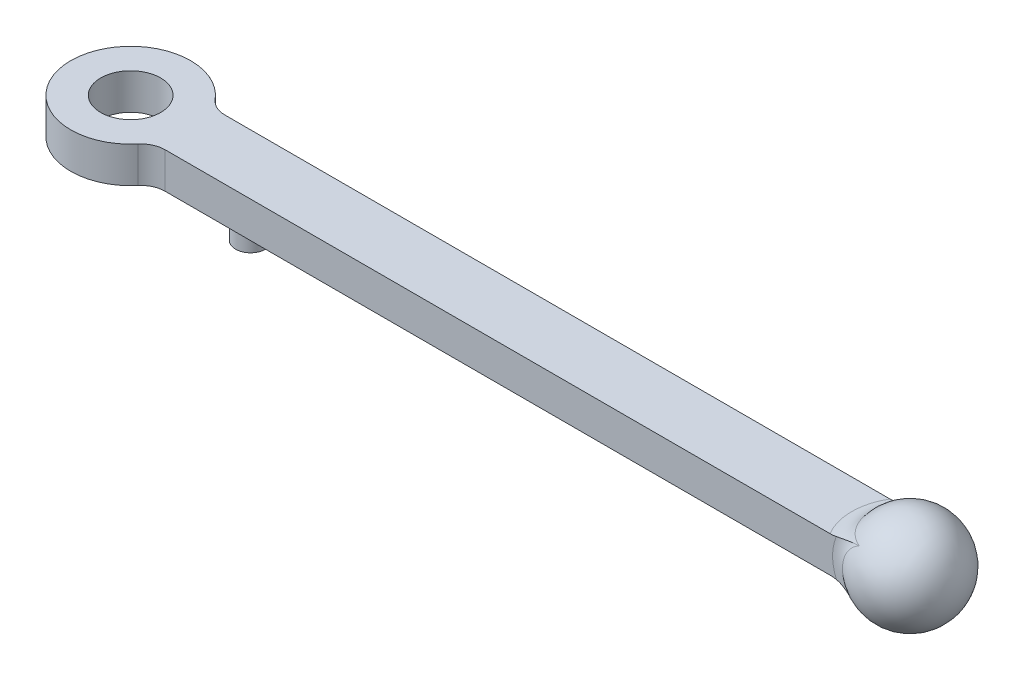
SolidWorks part; units mm, degrees
ref_plane "前视基准面" through (0, 0, 0) normal (0, 0, 1) x (1, 0, 0)
ref_plane "上视基准面" through (0, 0, 0) normal (0, 1, 0) x (1, 0, 0)
ref_plane "右视基准面" through (0, 0, 0) normal (1, 0, 0) x (0, 0, -1)
sketch "草图1" plane through (0, 0, 0) normal (0, 1, 0) x (1, 0, 0)
  line L0 (0, 0) -> (130, 0)
  line L2 (130, -5) -> (8.6603, -5)
  line L3 (130, -5) -> (130, 5)
  line L4 (130, 5) -> (8.6603, 5)
  line L5 (8.6603, -5) -> (8.6603, 5)
  circle A0 centre (0, 0) radius 10
  circle A1 centre (130, 0) radius 5
  dimension "D1" = 20
  dimension "D3" = 10
  dimension "D2" = 130
extrude "凸台-拉伸1" add sketch "草图1" along normal blind 6
ref_plane "基准面1" through (0, 3, 0) normal (0, 1, 0) x (1, 0, 0)
sketch "草图2" plane through (0, 3, 0) normal (0, 1, 0) x (1, 0, 0)
  line L0 (130, 0) -> (140, 0)
  line L1 (130, 0) -> (122, 0)
  line L2 (130, 5) -> (8.6603, 5)
  line L3 (8.6603, -5) -> (130, -5)
  line L4 (130, 5) -> (8.6603, 5)
  line L5 (8.6603, -5) -> (130, -5)
  line L6 (138, 0) -> (122, 0)
  circle A0 centre (130, 0) radius 10
  circle A1 centre (130, 0) radius 8
  arc A2 (8.6603, 5) -> (8.6603, -5) centre (0, 0) ccw
  arc A3 (130, -5) -> (130, 5) centre (130, 0) ccw
  arc A4 (8.6603, 5) -> (8.6603, -5) centre (0, 0) ccw
  arc A5 (130, -5) -> (130, 5) centre (130, 0) ccw
  dimension "D2" = 20
  dimension "D1" = 0
revolve "旋转6" add sketch "草图2" angle 360 about L0
fillet "圆角1" radius 4 6 edges at (8.6603, 3, -5) (122.5838, 6, 0) (123.755, 3, -5) (122.5838, 0, 0) (123.755, 3, 5) (8.6603, 3, 5)
sketch "草图3" plane through (0, 0, 0) normal (0, -1, 0) x (1, 0, 0)
  circle A0 centre (0, 0) radius 5
  dimension "D1" = 10
extrude "切除-拉伸1" cut sketch "草图3" against normal blind 6
sketch "草图4" plane through (0, 0, 0) normal (0, -1, 0) x (1, 0, 0)
  line L0 (0, 0) -> (20, 0)
  line L2 (10.7238, -5) -> (121.6334, -5)
  line L3 (121.6334, 5) -> (10.7238, 5)
  line L4 (10.7238, -5) -> (121.6334, -5)
  line L5 (121.6334, 5) -> (10.7238, 5)
  circle A0 centre (20, 0) radius 2.5
  arc A4 (121.6334, 5) -> (121.6334, -5) centre (130, 0) ccw
  arc A5 (7.6599, 6.4286) -> (10.7238, 5) centre (10.7238, 9) ccw
  arc A6 (7.6599, 6.4286) -> (7.6599, -6.4286) centre (0, 0) ccw
  arc A7 (10.7238, -5) -> (7.6599, -6.4286) centre (10.7238, -9) ccw
  arc A8 (121.6334, 5) -> (121.6334, -5) centre (130, 0) ccw
  arc A9 (7.6599, 6.4286) -> (10.7238, 5) centre (10.7238, 9) ccw
  arc A10 (7.6599, 6.4286) -> (7.6599, -6.4286) centre (0, 0) ccw
  arc A11 (10.7238, -5) -> (7.6599, -6.4286) centre (10.7238, -9) ccw
  dimension "D3" = 5
  dimension "D2" = 20
  dimension "D1" = 0
extrude "凸台-拉伸2" add sketch "草图4" along normal blind 5 contours A0
